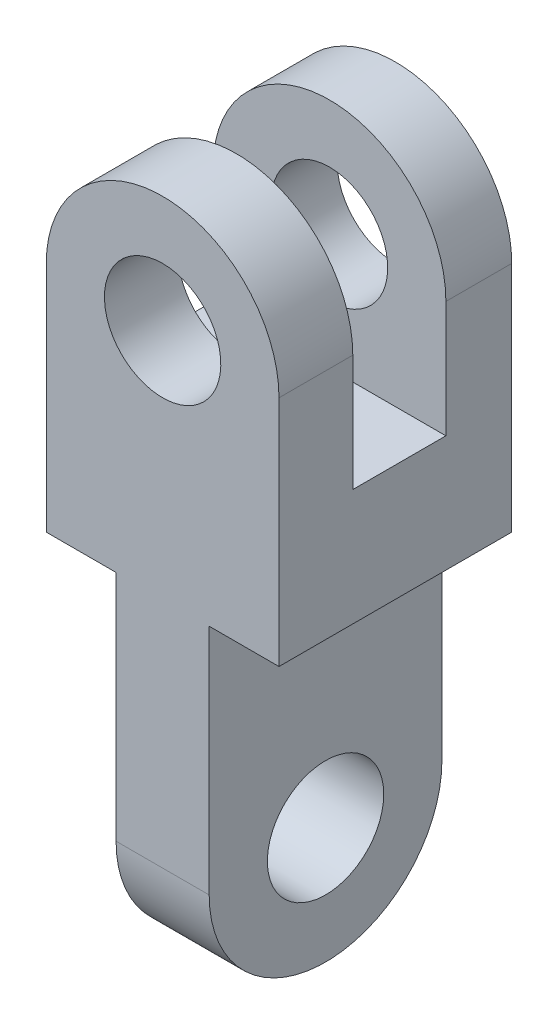
SolidWorks part; units mm, degrees
material "Delrin 2700 NC010, Low Viscosity Acetal Copolymer (SS)"
ref_plane "Front Plane" through (0, 0, 0) normal (0, 0, 1) x (1, 0, 0)
ref_plane "Top Plane" through (0, 0, 0) normal (0, 1, 0) x (1, 0, 0)
ref_plane "Right Plane" through (0, 0, 0) normal (1, 0, 0) x (0, 0, -1)
sketch "Sketch2" plane through (0, 0, 0) normal (1, 0, 0) x (0, 0, -1)
  line L0 (-50, 0) -> (50, 0)
  line L1 (50, 0) -> (50, -100)
  line L2 (-50, 0) -> (-50, -100)
  arc A0 (-50, -100) -> (50, -100) centre (0, -100) ccw
  circle A1 centre (0, -100) radius 25
  point P4 (0, 0)
  dimension "D3" = 50
  dimension "D1" = 100
  dimension "D2" = 100
extrude "Boss-Extrude1" add sketch "Sketch2" along normal mid plane 40
sketch "Sketch3" plane through (0, 0, -50) normal (0, 0, -1) x (-1, 0, 0)
  line L0 (-50, 0) -> (50, 0)
  line L1 (-50, 0) -> (-50, 100)
  line L2 (50, 100) -> (50, 0)
  arc A0 (-50, 100) -> (50, 100) centre (0, 100) cw
  circle A1 centre (0, 100) radius 25
  point P4 (0, 0)
  dimension "D3" = 50
  dimension "D1" = 100
  dimension "D2" = 100
extrude "Boss-Extrude2" add sketch "Sketch3" against normal up to surface (100 mm away) up to face at (0, -50, 50)
sketch "Sketch4" plane through (50, 0, 0) normal (1, 0, 0) x (0, 0, -1)
  line L0 (50, 150) -> (-50, 150) construction
  line L1 (21.7066, 150) -> (-18.2934, 150)
  line L2 (21.7066, 150) -> (21.7066, 50)
  line L3 (21.7066, 50) -> (-18.2934, 50)
  line L4 (-18.2934, 150) -> (-18.2934, 50)
  dimension "D2" = 100
  dimension "D1" = 40
extrude "Cut-Extrude1" cut sketch "Sketch4" against normal through all both and the other way through all
equation "\"a\"= 100mm"
equation "\"b\"= 30mm"
equation "\"D1@Sketch2\"=\"a\""
equation "\"e\"=40"
equation "\"D1@Boss-Extrude1\"=\"e\""
equation "\"D1@Sketch3\"= \"a\""
equation "\"D2@Sketch3\"=\"a\""
equation "\"D2@Sketch4\"=\"a\""
equation "\"D1@Sketch4\"=\"a\"-2*\"b\""
equation "\"h\"=50"
equation "\"D3@Sketch2\"=\"h\""
equation "\"D3@Sketch3\"=\"h\""
